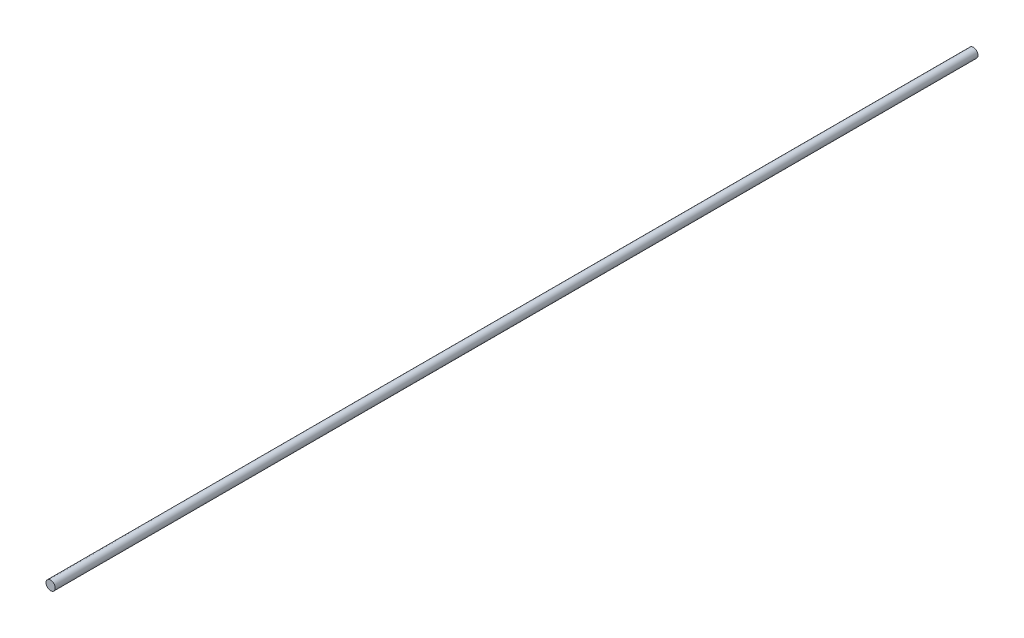
SolidWorks part; units mm, degrees
ref_plane "前视基准面" through (0, 0, 0) normal (0, 0, 1) x (1, 0, 0)
ref_plane "上视基准面" through (0, 0, 0) normal (0, 1, 0) x (1, 0, 0)
ref_plane "右视基准面" through (0, 0, 0) normal (1, 0, 0) x (0, 0, -1)
other "Configuration Table"
sketch "Sketch1" plane through (0, 0, 0) normal (0, 0, 1) x (1, 0, 0)
  circle A0 centre (0, 0) radius 5
  dimension "D1" = 10
extrude "Boss-Extrude1" add sketch "Sketch1" along normal blind 1000
